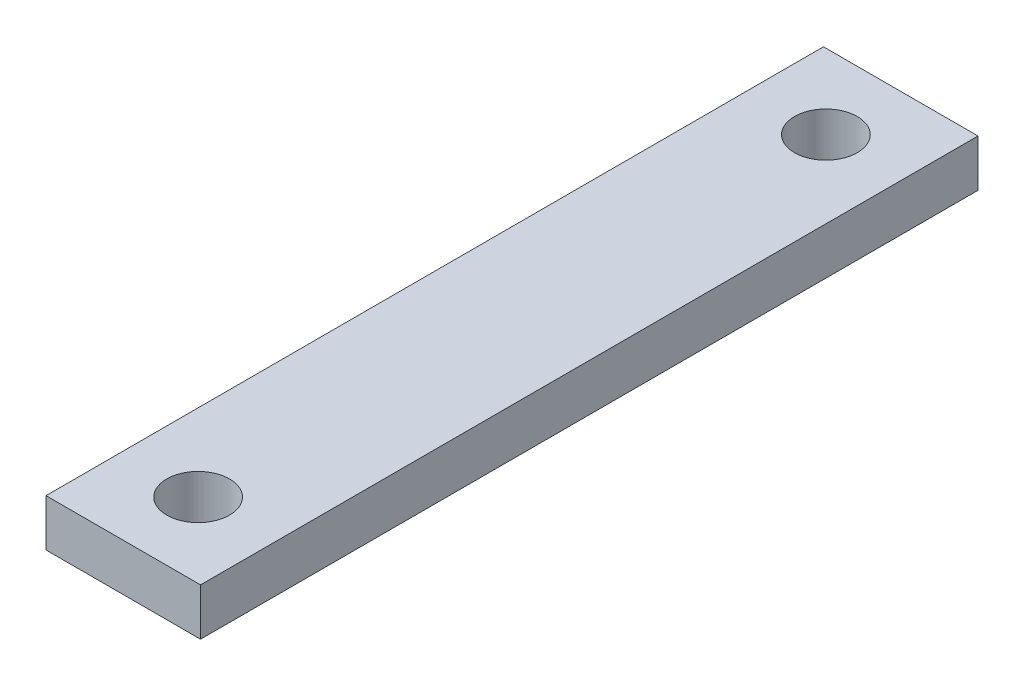
SolidWorks part; units mm, degrees
ref_plane "Front Plane" through (0, 0, 0) normal (0, 0, 1) x (1, 0, 0)
ref_plane "Top Plane" through (0, 0, 0) normal (0, 1, 0) x (1, 0, 0)
ref_plane "Right Plane" through (0, 0, 0) normal (1, 0, 0) x (0, 0, -1)
sketch "Sketch1" plane through (0, 0, 0) normal (0, 1, 0) x (1, 0, 0)
  line L0 (0, -20) -> (0, 20)
  line L2 (-4.9231, -24.7692) -> (4.9231, -24.7692)
  line L3 (-4.9231, -24.7692) -> (-4.9231, 24.7692)
  line L4 (-4.9231, 24.7692) -> (4.9231, 24.7692)
  line L5 (4.9231, -24.7692) -> (4.9231, 24.7692)
  line L6 (-4.9231, -24.7692) -> (4.9231, 24.7692) construction
  line L7 (-4.9231, 24.7692) -> (4.9231, -24.7692) construction
  circle A0 centre (0, 20) radius 2
  circle A1 centre (0, -20) radius 2
  point P4 (0, 0)
  point P7 (0, 0)
  dimension "D2" = 4
  dimension "D3" = 4
  dimension "D1" = 40
extrude "Boss-Extrude1" add sketch "Sketch1" along normal blind 3
